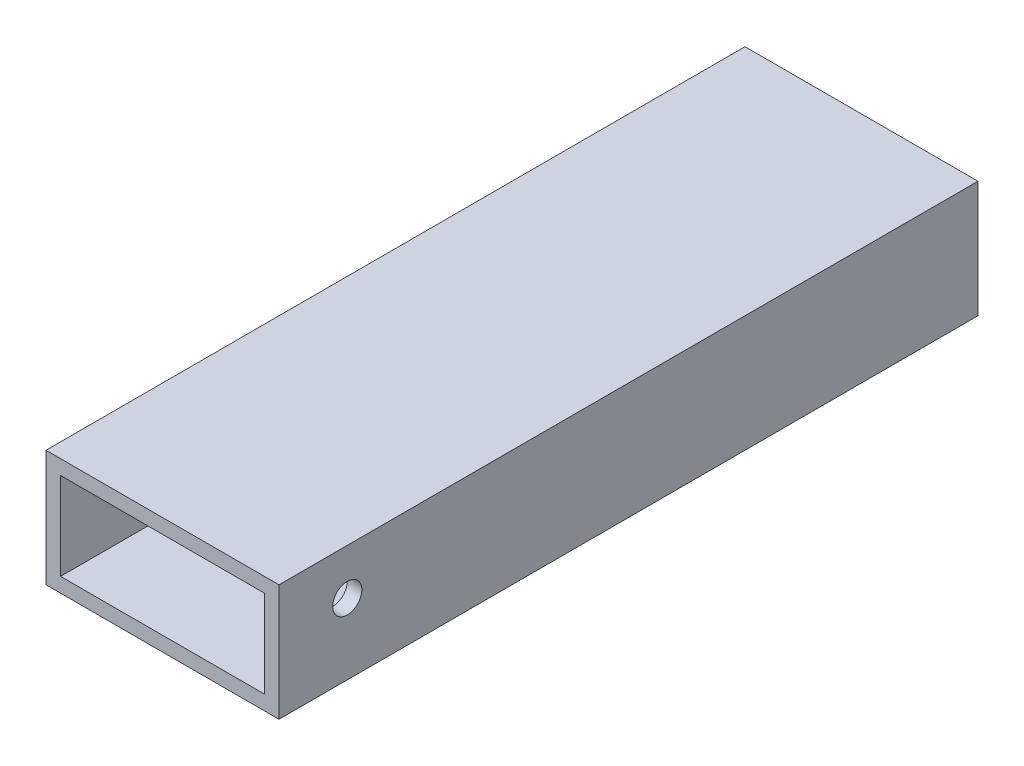
SolidWorks part; units mm, degrees
ref_plane "Front Plane" through (0, 0, 0) normal (0, 0, 1) x (1, 0, 0)
ref_plane "Top Plane" through (0, 0, 0) normal (0, 1, 0) x (1, 0, 0)
ref_plane "Right Plane" through (0, 0, 0) normal (1, 0, 0) x (0, 0, -1)
sketch "Sketch1" plane through (0, 0, 0) normal (0, 0, 1) x (1, 0, 0)
  line L0 (-22.225, -9.525) -> (22.225, -9.525)
  line L1 (-25.4, -12.7) -> (25.4, -12.7)
  line L2 (-25.4, -12.7) -> (-25.4, 12.7)
  line L3 (-25.4, 12.7) -> (25.4, 12.7)
  line L4 (25.4, -12.7) -> (25.4, 12.7)
  line L5 (22.225, -9.525) -> (22.225, 9.525)
  line L6 (-22.225, 9.525) -> (22.225, 9.525)
  line L7 (-22.225, -9.525) -> (-22.225, 9.525)
  dimension "D1" = 25.4
  dimension "D2" = 50.8
  dimension "D3" = 3.175
extrude "Boss-Extrude1" add sketch "Sketch1" along normal blind 152.4
sketch "Sketch2" plane through (25.4, 0, 0) normal (1, 0, 0) x (0, 0, -1)
  circle A1 centre (-137.5137, 2.7387) radius 3.175
extrude "Cut-Extrude1" cut sketch "Sketch2" against normal through all
